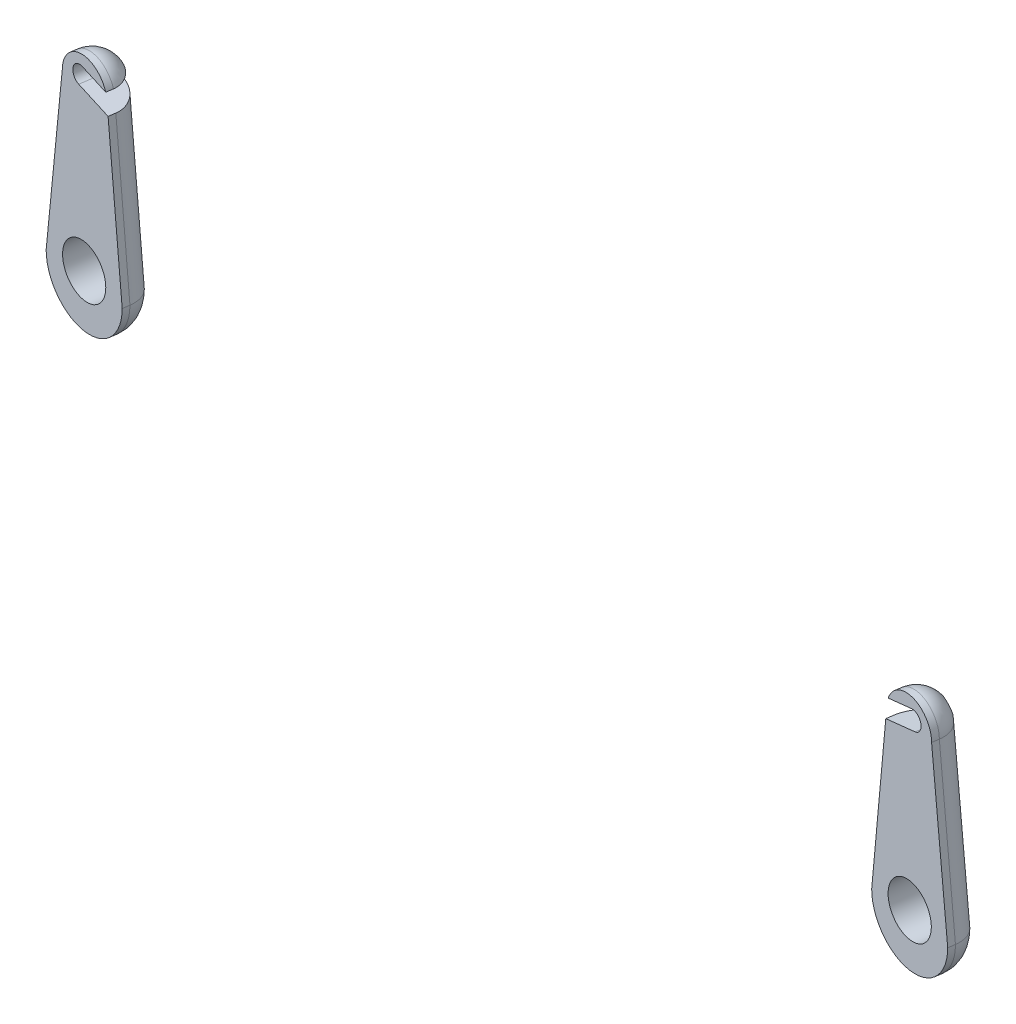
SolidWorks part; units mm, degrees
ref_plane "Front Plane" through (0, 0, 0) normal (0, 0, 1) x (1, 0, 0)
ref_plane "Top Plane" through (0, 0, 0) normal (0, 1, 0) x (1, 0, 0)
ref_plane "Right Plane" through (0, 0, 0) normal (1, 0, 0) x (0, 0, -1)
sketch "Sketch1" plane through (8.1146, -3.2834, -55.6766) normal (0.1442, 0, -0.9895) x (-0.9895, 0, -0.1442)
  line L0 (7.7839, 204.0844) -> (7.7839, 233.5484) construction
  line L1 (13.4843, 233.5484) -> (1.3539, 233.5484) construction
  line L2 (7.9153, 237.0844) -> (-3.6461, 237.0844) construction
  line L3 (-1.1061, 204.0844) -> (2.6653, 237.0844)
  line L4 (13.1653, 237.0844) -> (16.6739, 204.0844)
  line L6 (-3.6461, 243.0784) -> (-3.6461, 233.5484) construction
  line L8 (7.7839, 233.5484) -> (7.7839, 204.0844) construction
  line L9 (7.7839, 204.0844) -> (-3.6461, 204.0844) construction
  line L12 (7.7839, 204.0844) -> (7.7839, 233.5484) construction
  arc A1 (13.1653, 237.0844) -> (2.6653, 237.0844) centre (7.9153, 237.0844) ccw
  arc A2 (-1.1061, 204.0844) -> (16.6739, 204.0844) centre (7.7839, 204.0844) ccw
  dimension "D3" = 10.5
  dimension "D5" = 8.89
  dimension "D1" = 29.464
  dimension "D2" = 29.464
  dimension "D4" = 33
  dimension "D7" = 29.464
  dimension "D8" = 11.43
extrude "Base Extrude" add sketch "Sketch1" along normal blind 6.35
sketch "Sketch3" plane through (9.0304, -3.2834, -61.9602) normal (0.1442, 0, -0.9895) x (-0.9895, 0, -0.1442)
  line L0 (14.7164, 236.6382) -> (6.9306, 238.4771) construction
  line L1 (14.3026, 234.8864) -> (6.5168, 236.7253)
  line L2 (15.1301, 238.39) -> (7.3444, 240.2289)
  line L3 (9.1112, 236.4544) -> (9.1112, 237.9784) construction
  arc A0 (14.3026, 234.8864) -> (15.1301, 238.39) centre (14.7164, 236.6382) ccw
  arc A1 (7.3444, 240.2289) -> (6.5168, 236.7253) centre (6.9306, 238.4771) ccw
  circle A2 centre (9.1112, 237.9784) radius 1.524 construction
  point P3 (10.8235, 237.5577)
  dimension "D1" = 1.8
  dimension "D2" = 8
ref_plane "Rear Mirror Plane " through (-103.2134, 0, -15.0429) normal (0.9895, 0, 0.1442) x (0.1442, 0, -0.9895)
fillet "Fillet1" radius 5 4 edges at (1.1978, 239.051, -63.1018) (1.3279, 191.911, -63.0828) (-5.7332, 217.301, -64.112) (8.259, 217.301, -62.0727)
extrude "Cut-Extrude1" cut sketch "Sketch3" against normal up to surface (6.35 mm away) up to face at (0.3471, 216.391, -56.8087)
mirror "Mirror2" about plane through (-103.2134, 0, -15.0429) normal (0.9895, 0, 0.1442) of bodies 109
sketch "Sketch4" plane through (9.0304, 0, -61.9602) normal (0.1442, 0, -0.9895) x (-0.9895, 0, -0.1442)
  line L0 (2.7459, 202.201) -> (7.7839, 202.201) construction
  circle A0 centre (7.7839, 202.201) radius 5.0381 construction
  circle A1 centre (7.7839, 202.201) radius 5.05
  dimension "D1" = 10.1
extrude "Cut-Extrude2" cut sketch "Sketch4" against normal up to surface (6.35 mm away) up to face at (0.23, 224.1467, -56.8258)
mirror "Mirror3" about plane through (-103.2134, 0, -15.0429) normal (0.9895, 0, 0.1442) of "Cut-Extrude2"
